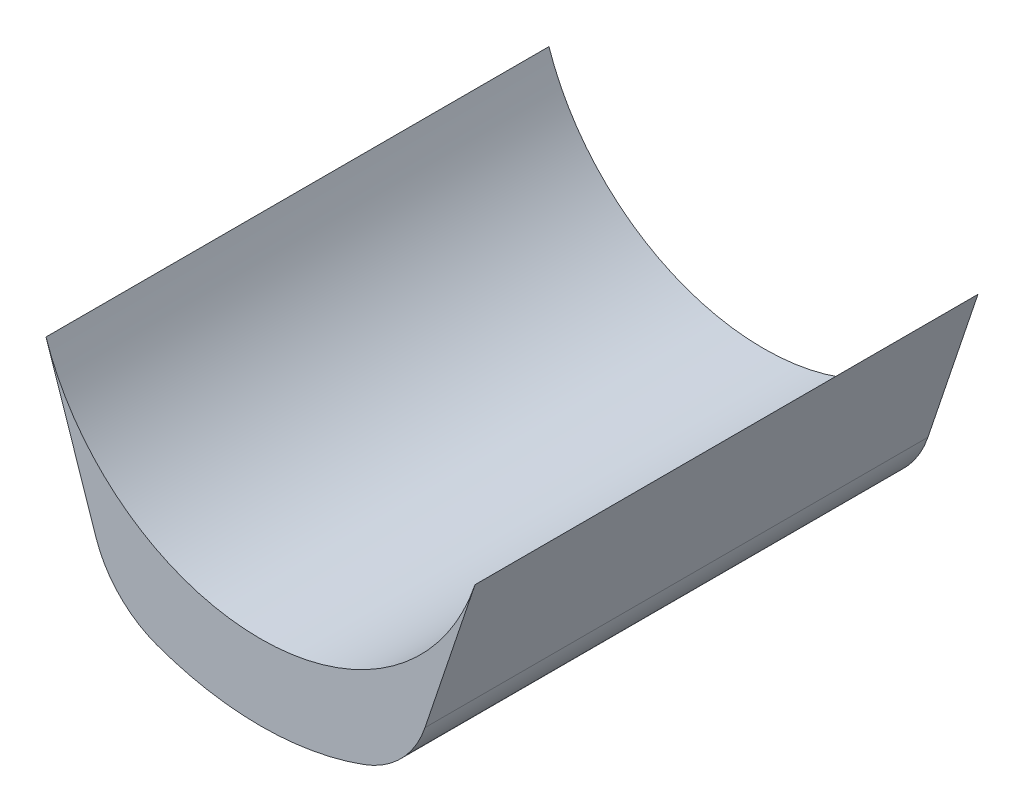
SolidWorks part; units mm, degrees
ref_plane "Front Plane" through (0, 0, 0) normal (0, 0, 1) x (1, 0, 0)
ref_plane "Top Plane" through (0, 0, 0) normal (0, 1, 0) x (1, 0, 0)
ref_plane "Right Plane" through (0, 0, 0) normal (1, 0, 0) x (0, 0, -1)
sketch "Sketch1" plane through (0, 0, 0) normal (0, 0, 1) x (1, 0, 0)
  circle A0 centre (0, 0) radius 57.15 construction
  dimension "D1" = 114.3
sketch "Sketch2" plane through (0, 0, 0) normal (0, 0, 1) x (1, 0, 0)
  line L0 (-54.168, -18.2194) -> (-38.1, -65.9911)
  line L1 (54.168, -18.2194) -> (38.1, -65.9911)
  arc A0 (-54.168, -18.2194) -> (54.168, -18.2194) centre (0, 0) ccw
  arc A1 (-38.1, -65.9911) -> (38.1, -65.9911) centre (0, 0) ccw
  dimension "D1" = 114.3
  dimension "D2" = 152.4
  dimension "D3" = 38.1
  dimension "D4" = 38.1
extrude "Boss-Extrude1" add sketch "Sketch2" along normal blind 127
fillet "Fillet1" radius 25.4 2 edges at (-38.1, -65.9911, 63.5) (38.1, -65.9911, 63.5)
